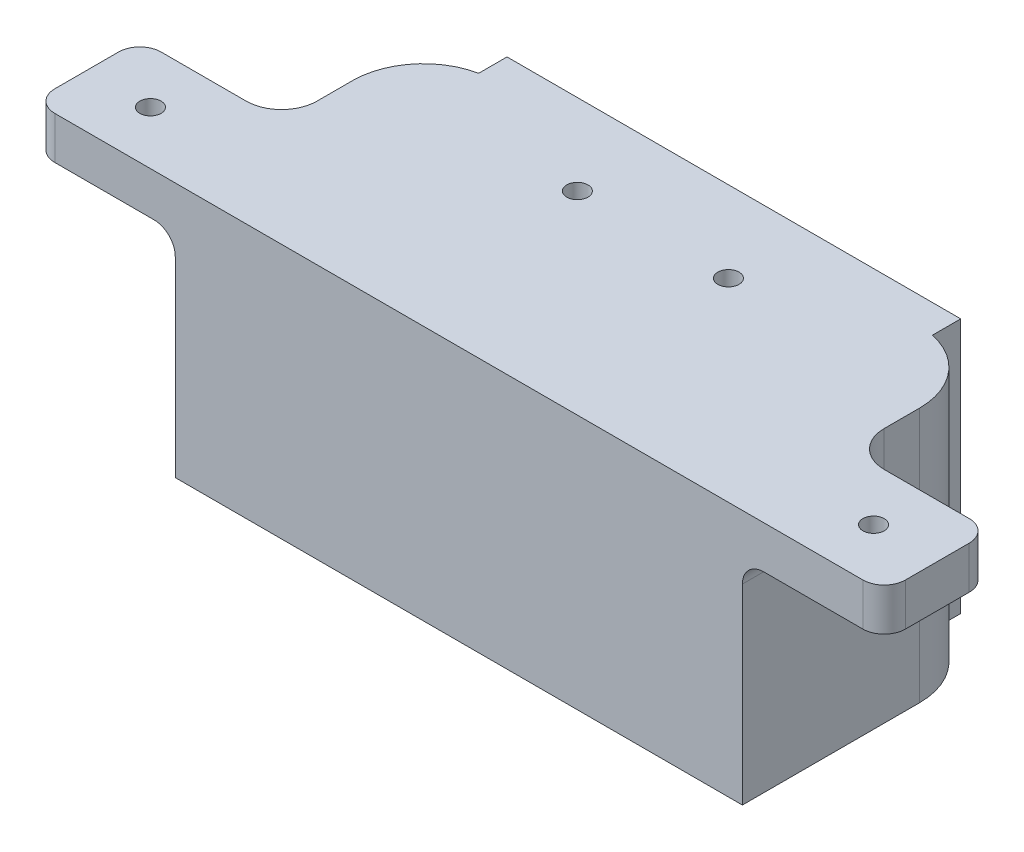
SolidWorks part; units mm, degrees
ref_plane "Alzado" through (0, 0, 0) normal (0, 0, 1) x (1, 0, 0)
ref_plane "Planta" through (0, 0, 0) normal (0, 1, 0) x (1, 0, 0)
ref_plane "Vista lateral" through (0, 0, 0) normal (1, 0, 0) x (0, 0, -1)
sketch "Croquis1" plane through (0, 0, 0) normal (0, 1, 0) x (1, 0, 0)
  line L0 (-58.0166, 0) -> (58.0166, 0) construction
  line L5 (40, -25) -> (40, 0)
  line L6 (11.3137, 4) -> (20.8348, 4)
  line L7 (0, 33.1459) -> (0, -45.5761) construction
  line L8 (-40, -25) -> (-40, 0)
  line L9 (-11.3137, 4) -> (-20.8348, 4)
  line L10 (-40, -25) -> (40, -25)
  arc A1 (11.3137, 4) -> (-11.3137, 4) centre (0, 0) ccw
  arc A2 (40, 0) -> (20.8348, 4) centre (30, 0) ccw
  arc A3 (-40, 0) -> (-20.8348, 4) centre (-30, 0) cw
  point P3 (0, 0)
  dimension "D1" = 20
  dimension "D2" = 24
  dimension "D3" = 30
  dimension "D4" = 4
  dimension "D5" = 25
extrude "Saliente-Extruir1" add sketch "Croquis1" along normal blind 30
sketch "Croquis3" plane through (0, 30, 0) normal (0, 1, 0) x (1, 0, 0)
  line L0 (-30, 0) -> (-30, 16.5211) construction
  line L1 (-32, 9.798) -> (-32, 13.798)
  line L2 (-32, 13.798) -> (-28, 13.798)
  line L3 (-28, 9.798) -> (-28, 13.798)
  line L4 (0, -55) -> (0, 55) construction
  line L5 (28, 9.798) -> (28, 13.798)
  line L6 (32, 13.798) -> (28, 13.798)
  line L7 (32, 9.798) -> (32, 13.798)
  arc A0 (-20.8348, 4) -> (-40, 0) centre (-30, 0) ccw construction
  arc A1 (-28, 9.798) -> (-32, 9.798) centre (-30, 0) ccw
  arc A2 (28, 9.798) -> (32, 9.798) centre (30, 0) cw
  point P10 (-30, 13.798)
  dimension "D1" = 4
  dimension "D2" = 4
extrude "Saliente-Extruir2" add sketch "Croquis3" against normal up to surface (30 mm away) up to face at (0, 0, 1.3027)
sketch "Croquis4" plane through (0, 30, 0) normal (0, 1, 0) x (1, 0, 0)
  line L0 (-30.5, 7.4833) -> (-30.5, 14.6548)
  line L1 (-30, 0) -> (-30, 16.6168) construction
  line L2 (-30.5, 14.6548) -> (-29.5, 14.6548)
  line L3 (-29.5, 7.4833) -> (-29.5, 14.6548)
  line L4 (0, -55) -> (0, 55) construction
  line L5 (29.5, 7.4833) -> (29.5, 14.6548)
  line L6 (30.5, 14.6548) -> (29.5, 14.6548)
  line L7 (30.5, 7.4833) -> (30.5, 14.6548)
  arc A1 (-30.5, 7.4833) -> (-29.5, 7.4833) centre (-30, 0) ccw
  arc A2 (30.5, 7.4833) -> (29.5, 7.4833) centre (30, 0) cw
  point P8 (-30, 14.6548)
  point P16 (30, 14.6548)
  dimension "D1" = 15
  dimension "D2" = 1
extrude "Cortar-Extruir2" cut sketch "Croquis4" against normal through all both and the other way through all
sketch "Croquis5" plane through (0, 30, 0) normal (0, 1, 0) x (1, 0, 0)
  line L0 (-20, 0) -> (-20, -10)
  line L1 (-20, -10) -> (20, -10)
  line L2 (0, 31.6012) -> (0, -31.6012) construction
  line L3 (-20, -10) -> (-30, -10) construction
  line L7 (20, 0) -> (20, -10)
  line L8 (-20.8348, 4) -> (-20.8348, 13.996)
  line L9 (-20.8348, 13.996) -> (20.8348, 13.996)
  line L10 (20.8348, 13.996) -> (20.8348, 4)
  arc A0 (11.3137, 4) -> (-11.3137, 4) centre (0, 0) ccw construction
  arc A3 (-32, 9.798) -> (-40, 0) centre (-30, 0) ccw construction
  arc A4 (-32, 9.798) -> (-40, 0) centre (-30, 0) ccw construction
  arc A5 (-20, 0) -> (-20.8348, 4) centre (-30, 0) ccw
  arc A6 (-32, 9.798) -> (-40, 0) centre (-30, 0) ccw construction
  arc A7 (20, 0) -> (20.8348, 4) centre (30, 0) cw
  point P9 (0, 0)
  point P16 (0, -10)
extrude "Cortar-Extruir3" cut sketch "Croquis5" against normal blind 30
sketch "Croquis12" plane through (0, 30, 0) normal (0, 1, 0) x (1, 0, 0)
  line L3 (40, -25) -> (-40, -25)
  line L4 (-40, -25) -> (-57, -25)
  line L5 (-60, -22) -> (-60, -13)
  line L6 (-57, -10) -> (-45, -10)
  line L7 (0, 14.1113) -> (0, -25) construction
  line L8 (40, -25) -> (57, -25)
  line L9 (60, -22) -> (60, -13)
  line L10 (57, -10) -> (45, -10)
  line L11 (-40, -5) -> (-40, 0)
  line L12 (-32, 13.798) -> (32, 13.798)
  line L13 (40, -5) -> (40, 0)
  line L14 (-32, 9.798) -> (-32, 13.798)
  line L15 (-32, 13.798) -> (-32, 9.798) construction
  line L16 (32, 9.798) -> (32, 13.798)
  arc A0 (-60, -13) -> (-57, -10) centre (-57, -13) cw
  arc A1 (-57, -25) -> (-60, -22) centre (-57, -22) cw
  arc A2 (-40, -5) -> (-45, -10) centre (-45, -5) cw
  arc A3 (57, -25) -> (60, -22) centre (57, -22) ccw
  arc A4 (60, -13) -> (57, -10) centre (57, -13) ccw
  arc A5 (40, -5) -> (45, -10) centre (45, -5) ccw
  arc A6 (-32, 9.798) -> (-40, 0) centre (-30, 0) ccw
  arc A7 (32, 9.798) -> (40, 0) centre (30, 0) cw
  point P12 (-60, -10)
  point P15 (-60, -25)
  dimension "D3" = 3
  dimension "D4" = 3
  dimension "D1" = 5
  dimension "D2" = 15
extrude "Saliente-Extruir3" add sketch "Croquis12" along normal blind 6
sketch "Croquis13" plane through (0, 36, 0) normal (0, 1, 0) x (1, 0, 0)
  line L0 (51, -10) -> (51, -25) construction
  line L1 (57, -10) -> (45, -10) construction
  line L2 (-57, -25) -> (57, -25) construction
  line L5 (-10.6555, 3.8751) -> (-10.6555, -10) construction
  line L7 (-20, -10) -> (20, -10) construction
  circle A0 centre (51, -17.5) radius 1.5
  circle A1 centre (-51, -17.5) radius 1.5
  circle A2 centre (-10.6555, 2.3751) radius 1.5
  circle A3 centre (10.6555, 2.3751) radius 1.5
  dimension "D1" = 3
  dimension "D2" = 3
extrude "Cortar-Extruir6" cut sketch "Croquis13" against normal through all
fillet "Redondeo3" radius 3 1 edges at (40, 30, 15)
fillet "Redondeo4" radius 3 1 edges at (-40, 30, 15)
